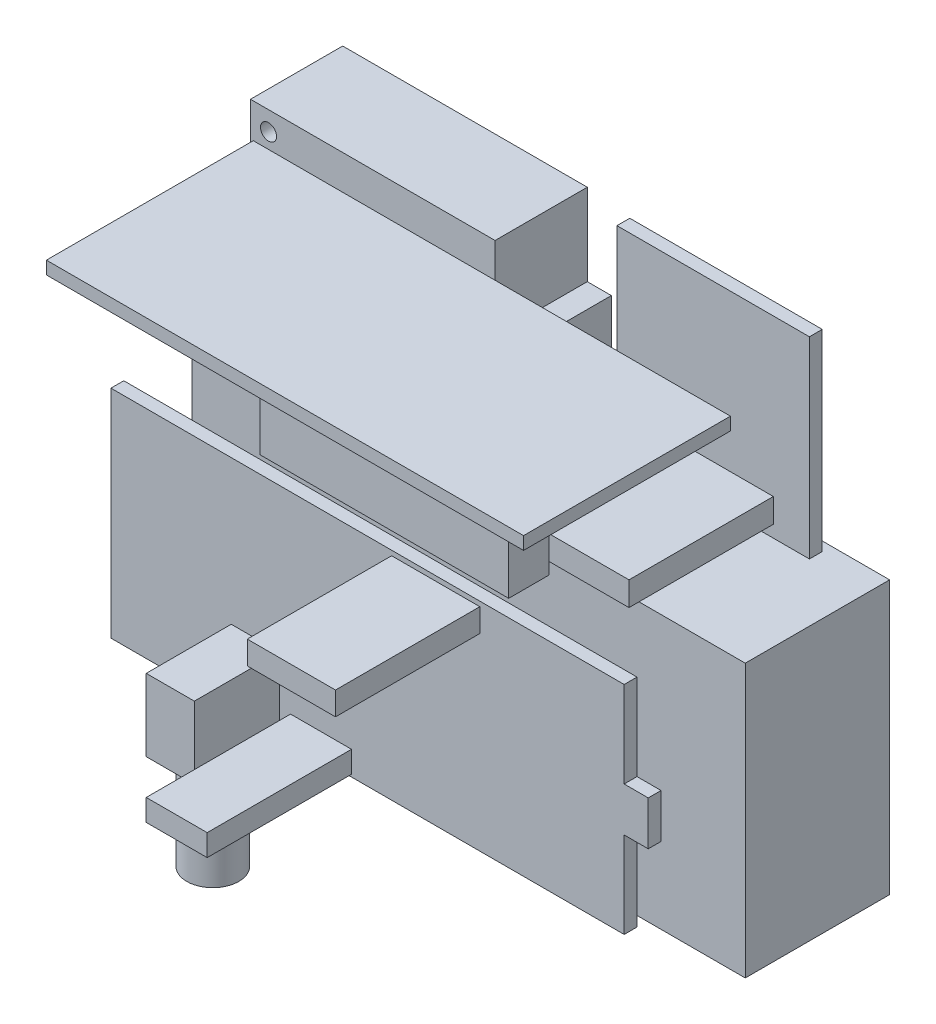
SolidWorks part; units mm, degrees
ref_plane "前视基准面" through (0, 0, 0) normal (0, 0, 1) x (1, 0, 0)
ref_plane "上视基准面" through (0, 0, 0) normal (0, 1, 0) x (1, 0, 0)
ref_plane "右视基准面" through (0, 0, 0) normal (1, 0, 0) x (0, 0, -1)
other "Configuration Table"
sketch "Battery holder 69 x 34 x 18 profile" plane through (0, 0, 0) normal (0, 0, 1) x (1, 0, 0)
  line L0 (-34.5, -29.75) -> (34.5, -29.75)
  line L1 (34.5, -29.75) -> (34.5, 4.25)
  line L2 (34.5, 4.25) -> (-34.5, 4.25)
  line L3 (-34.5, 4.25) -> (-34.5, -29.75)
extrude "Battery holder 69 x 34 x 18" add sketch "Battery holder 69 x 34 x 18 profile" along normal blind 18 from offset 4 separate body
sketch "YBX board 24 x 24 profile" plane through (0, 0, 0) normal (0, 0, 1) x (1, 0, 0)
  line L0 (4.5, 5.5) -> (28.5, 5.5)
  line L1 (28.5, 5.5) -> (28.5, 29.5)
  line L2 (28.5, 29.5) -> (4.5, 29.5)
  line L3 (4.5, 29.5) -> (4.5, 5.5)
extrude "YBX board 24 x 24" add sketch "YBX board 24 x 24 profile" along normal blind 1.6 from offset 6.4 separate body
sketch "YBX jumper allowance profile" plane through (0, 0, 0) normal (0, 0, 1) x (1, 0, 0)
  line L0 (9, 7) -> (24, 7)
  line L1 (24, 7) -> (24, 10)
  line L2 (24, 10) -> (9, 10)
  line L3 (9, 10) -> (9, 7)
extrude "YBX jumper allowance" add sketch "YBX jumper allowance profile" along normal blind 18 from offset 8 separate body
sketch "GNSS 11.5 mm high - 3 mm projection - D2 mount holes profile" plane through (0, 0, 0) normal (0, 0, 1) x (1, 0, 0)
  line L0 (-31.3, 4.7) -> (-0.8, 4.7)
  line L1 (-0.8, 4.7) -> (-0.8, 13)
  line L2 (-0.8, 13) -> (2.2, 13)
  line L3 (2.2, 13) -> (2.2, 20)
  line L4 (2.2, 20) -> (-0.8, 20)
  line L5 (-0.8, 20) -> (-0.8, 30.2)
  line L6 (-0.8, 30.2) -> (-31.3, 30.2)
  line L7 (-31.3, 30.2) -> (-31.3, 4.7)
  circle A0 centre (-29.05, 7) radius 1
  circle A1 centre (-29.05, 27.8) radius 1
extrude "GNSS 11.5 mm high - 3 mm projection - D2 mount holes" add sketch "GNSS 11.5 mm high - 3 mm projection - D2 mount holes profile" along normal blind 11.5 from offset 6.4 separate body
sketch "Power board 59.5 x 25.8 profile" plane through (0, 0, 0) normal (0, 0, 1) x (1, 0, 0)
  line L0 (-29.75, 25.5) -> (29.75, 25.5)
  line L1 (29.75, 25.5) -> (29.75, 27.1)
  line L2 (29.75, 27.1) -> (-29.75, 27.1)
  line L3 (-29.75, 27.1) -> (-29.75, 25.5)
extrude "Power board 59.5 x 25.8" add sketch "Power board 59.5 x 25.8 profile" along normal blind 25.8 from offset 19.1 separate body
sketch "Power horizontal connector allowance profile" plane through (0, 0, 0) normal (0, 0, 1) x (1, 0, 0)
  line L0 (-13, 9.5) -> (18, 9.5)
  line L1 (18, 9.5) -> (18, 25.5)
  line L2 (18, 25.5) -> (-13, 25.5)
  line L3 (-13, 25.5) -> (-13, 9.5)
extrude "Power horizontal connector allowance" add sketch "Power horizontal connector allowance profile" along normal blind 5 from offset 30 separate body
sketch "EoRa 64 x 27 - top projection 3 x 5.5 profile" plane through (0, 0, 0) normal (0, 0, 1) x (1, 0, 0)
  line L0 (-32, -20) -> (32, -20)
  line L1 (32, -20) -> (32, -9.25)
  line L2 (32, -9.25) -> (35, -9.25)
  line L3 (35, -9.25) -> (35, -3.75)
  line L4 (35, -3.75) -> (32, -3.75)
  line L5 (32, -3.75) -> (32, 7)
  line L6 (32, 7) -> (-32, 7)
  line L7 (-32, 7) -> (-32, -20)
extrude "EoRa 64 x 27 - top projection 3 x 5.5" add sketch "EoRa 64 x 27 - top projection 3 x 5.5 profile" along normal blind 1.6 from offset 33 separate body
sketch "EoRa antenna housing 6 x 9 x 10.6 profile" plane through (0, 0, 0) normal (0, 0, 1) x (1, 0, 0)
  line L0 (-17, -20) -> (-11, -20)
  line L1 (-11, -20) -> (-11, -11)
  line L2 (-11, -11) -> (-17, -11)
  line L3 (-17, -11) -> (-17, -20)
extrude "EoRa antenna housing 6 x 9 x 10.6" add sketch "EoRa antenna housing 6 x 9 x 10.6 profile" along normal blind 10.6 from offset 34.6 separate body
sketch "D6.5 antenna passage gauge - length not a part dimension profile" plane through (0, -20, 0) normal (0, -1, 0) x (1, 0, 0)
  circle A0 centre (-14, 39.9) radius 3.25
extrude "D6.5 antenna passage gauge - length not a part dimension" add sketch "D6.5 antenna passage gauge - length not a part dimension profile" along normal blind 13 separate body
sketch "EoRa jumper allowance A profile" plane through (0, 0, 0) normal (0, 0, 1) x (1, 0, 0)
  line L0 (-9.6, -19.7) -> (-2, -19.7)
  line L1 (-2, -19.7) -> (-2, -17)
  line L2 (-2, -17) -> (-9.6, -17)
  line L3 (-9.6, -17) -> (-9.6, -19.7)
extrude "EoRa jumper allowance A" add sketch "EoRa jumper allowance A profile" along normal blind 18 from offset 34.6 separate body
sketch "EoRa jumper allowance B profile" plane through (0, 0, 0) normal (0, 0, 1) x (1, 0, 0)
  line L0 (3, 3.5) -> (14, 3.5)
  line L1 (14, 3.5) -> (14, 6.4)
  line L2 (14, 6.4) -> (3, 6.4)
  line L3 (3, 6.4) -> (3, 3.5)
extrude "EoRa jumper allowance B" add sketch "EoRa jumper allowance B profile" along normal blind 18 from offset 34.6 separate body
